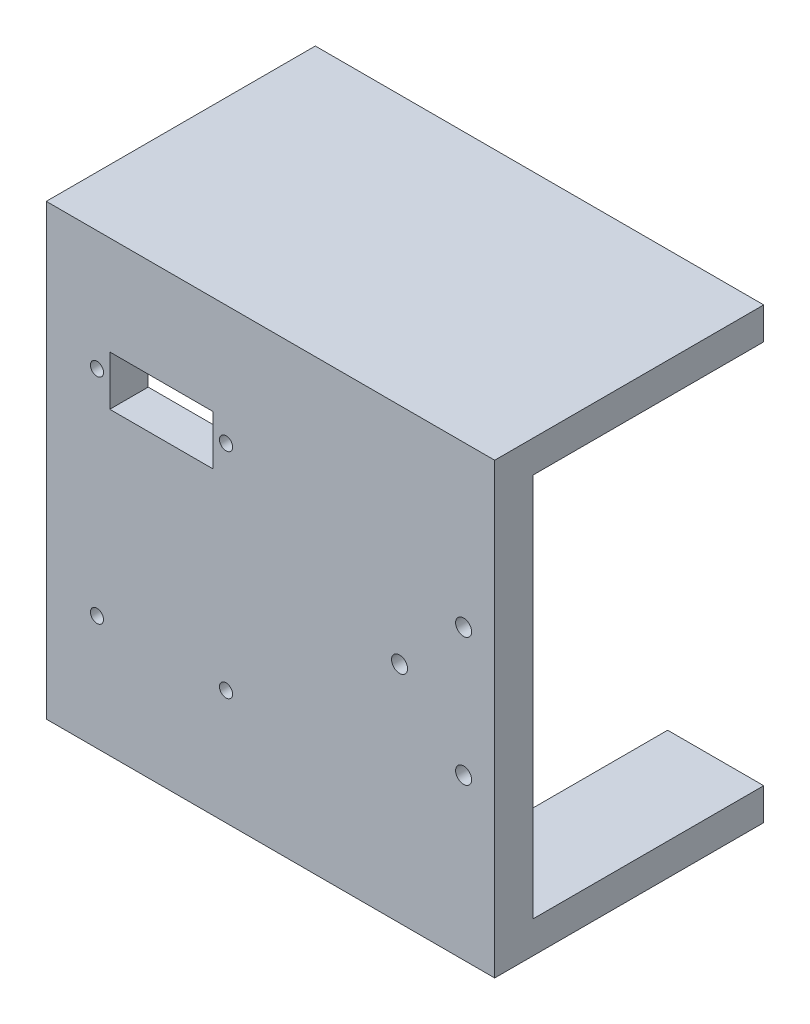
SolidWorks part; units mm, degrees
ref_plane "前视基准面" through (0, 0, 0) normal (0, 0, 1) x (1, 0, 0)
ref_plane "上视基准面" through (0, 0, 0) normal (0, 1, 0) x (1, 0, 0)
ref_plane "右视基准面" through (0, 0, 0) normal (1, 0, 0) x (0, 0, -1)
sketch "Sketch1" plane through (0, 0, 0) normal (0, 0, 1) x (1, 0, 0)
  line L1 (-39.3825, 46.8725) -> (30.6175, 46.8725)
  line L2 (-39.3825, 46.8725) -> (-39.3825, 41.8725)
  line L3 (-39.3825, 41.8725) -> (30.6175, 41.8725)
  line L4 (30.6175, 46.8725) -> (30.6175, 41.8725)
  line L5 (15.6175, -18.1275) -> (30.6175, -18.1275)
  line L6 (15.6175, -18.1275) -> (15.6175, -23.1275)
  line L7 (15.6175, -23.1275) -> (30.6175, -23.1275)
  line L8 (30.6175, -18.1275) -> (30.6175, -23.1275)
  dimension "D1" = 70
  dimension "D2" = 5
  dimension "D3" = 15
  dimension "D4" = 5
  dimension "D5" = 70
extrude "Boss-Extrude1" add sketch "Sketch1" along normal blind 36
sketch "Sketch2" plane through (30.6175, 0, 0) normal (1, 0, 0) x (0, 0, -1)
  line L0 (-36, -23.1275) -> (0, -23.1275) construction
  line L1 (-36, 46.8725) -> (-42, 46.8725)
  line L2 (-36, 46.8725) -> (-36, -23.1275)
  line L3 (-36, -23.1275) -> (-42, -23.1275)
  line L4 (-42, 46.8725) -> (-42, -23.1275)
  dimension "D1" = 6
extrude "Boss-Extrude2" add sketch "Sketch2" against normal up to surface (70 mm away) up to face at (-39.3825, 44.3725, 18)
sketch "Sketch3" plane through (0, 0, 0) normal (0, 0, -1) x (-1, 0, 0)
  line L0 (-30.6175, -23.1275) -> (-30.6175, -18.1275) construction
  line L1 (-30.6175, 41.8725) -> (-30.6175, 46.8725) construction
  line L2 (39.3825, 46.8725) -> (39.3825, 41.8725) construction
  line L3 (-30.6175, 46.8725) -> (39.3825, 46.8725) construction
  line L4 (-15.6175, -23.1275) -> (-30.6175, -23.1275) construction
  circle A0 centre (-23.6175, -20.6275) radius 1
  circle A1 centre (-23.6175, 44.3725) radius 1
  circle A2 centre (32.3825, 44.3725) radius 1
  dimension "D1" = 2
  dimension "D2" = 2
  dimension "D3" = 2
  dimension "D4" = 7
  dimension "D5" = 7
  dimension "D6" = 7
  dimension "D7" = 2.5
  dimension "D8" = 2.5
  dimension "D9" = 2.5
hole_wizard "M2 Tapped Hole1" positions "3DSketch1" profile "Sketch5" tap size "M2" standard "GB"
sketch3d "3DSketch1"
  point P0 (23.6175, 44.3725, 0)
  point P3 (-32.3825, 44.3725, 0)
  point P6 (23.6175, -20.6275, 0)
sketch "Sketch5" plane through (23.6175, 44.3725, 0) normal (1, 0, 0) x (0, 1, 0)
  line L0 (0, 0) -> (0, 5.4807)
  line L1 (0, 5.4807) -> (0.8, 5)
  line L2 (0.8, 5) -> (0.8, 0)
  line L5 (0.8, 0) -> (0, 0)
  line L10 (0, 5.4807) -> (-0.8, 5) construction
  line L11 (0, -6.35) -> (0, 107.95) construction
  dimension "Tap Drill Dia." = 1.6
  dimension "Tap Drill Depth" = 5
  dimension "Drill Angle" = 118
cosmetic thread "Hole Thread1" parameters "D1"=4, "D2"=2
cosmetic thread "Hole Thread2" parameters "D1"=4, "D2"=2
cosmetic thread "Hole Thread3" parameters "D1"=4, "D2"=2
sketch "Sketch6" plane through (0, 0, 42) normal (0, 0, 1) x (1, 0, 0)
  line L0 (30.6175, 46.8725) -> (30.6175, -23.1275) construction
  line L1 (10.6175, -70.6275) -> (30.6175, -70.6275) construction
  line L2 (10.6175, -70.6275) -> (10.6175, 94.3725) construction
  line L3 (10.6175, 94.3725) -> (30.6175, 94.3725) construction
  line L4 (30.6175, -70.6275) -> (30.6175, 94.3725) construction
  line L5 (-22.2951, -23.1275) -> (-22.2951, 46.8725) construction
  line L6 (-39.3825, -23.1275) -> (30.6175, -23.1275) construction
  line L7 (-39.3825, 46.8725) -> (30.6175, 46.8725) construction
  line L8 (25.7675, 1.8725) -> (25.7675, 21.8725) construction
  circle A0 centre (25.7675, 1.8725) radius 1.5
  circle A1 centre (25.7675, 21.8725) radius 1.5
  circle A2 centre (15.7675, 11.8725) radius 1.5
  point P12 (-22.2951, 11.8725)
  point P13 (10.6175, 11.8725)
  point P16 (25.7675, 11.8725)
  dimension "D3" = 3
  dimension "D4" = 3
  dimension "D5" = 3
  dimension "D1" = 165
  dimension "D2" = 20
  dimension "D6" = 10
hole_wizard "M3 Tapped Hole1" positions "3DSketch2" profile "Sketch7" tap size "M3" standard "GB" end condition through all
sketch3d "3DSketch2"
  point P0 (15.7675, 11.8725, 42)
  point P3 (25.7675, 1.8725, 42)
  point P6 (25.7675, 21.8725, 42)
sketch "Sketch7" plane through (15.7675, 11.8725, 42) normal (1, 0, 0) x (0, -1, 0)
  line L0 (0, 0) -> (0, 42)
  line L1 (0, 42) -> (1.25, 42)
  line L2 (1.25, 42) -> (1.25, 0)
  line L5 (1.25, 0) -> (0, 0)
  line L11 (0, -6.35) -> (0, 107.95) construction
  dimension "Thru Tap Drill Dia." = 2.5
  dimension "Thru Tap Drill Depth" = 42
cosmetic thread "Hole Thread4" parameters "D2"=3
cosmetic thread "Hole Thread5" parameters "D2"=3
cosmetic thread "Hole Thread6" parameters "D2"=3
sketch "Sketch8" plane through (0, 0, 42) normal (0, 0, 1) x (1, 0, 0)
  line L1 (-31.4693, 28.1911) -> (-11.3193, 28.1911) construction
  line L2 (-31.4693, 28.1911) -> (-31.4693, -5.2089) construction
  line L3 (-31.4693, -5.2089) -> (-11.3193, -5.2089) construction
  line L4 (-11.3193, 28.1911) -> (-11.3193, -5.2089) construction
  circle A0 centre (-31.4693, 28.1911) radius 1.25
  circle A1 centre (-31.4693, -5.2089) radius 1.25
  circle A2 centre (-11.3193, -5.2089) radius 1.25
  circle A3 centre (-11.3193, 28.1911) radius 1.25
  dimension "D3" = 2.5
  dimension "D4" = 2.5
  dimension "D5" = 2.5
  dimension "D6" = 2.5
  dimension "D1" = 20.15
  dimension "D2" = 33.4
hole_wizard "M2.5 Tapped Hole1" positions "3DSketch3" profile "Sketch9" tap size "M2.5" standard "GB" end condition through all
sketch3d "3DSketch3"
  point P0 (-31.4693, 28.1911, 42)
  point P3 (-11.3193, 28.1911, 42)
  point P6 (-11.3193, -5.2089, 42)
  point P9 (-31.4693, -5.2089, 42)
sketch "Sketch9" plane through (-31.4693, 28.1911, 42) normal (1, 0, 0) x (0, -1, 0)
  line L0 (0, 0) -> (0, 42)
  line L1 (0, 42) -> (1.025, 42)
  line L2 (1.025, 42) -> (1.025, 0)
  line L5 (1.025, 0) -> (0, 0)
  line L11 (0, -6.35) -> (0, 107.95) construction
  dimension "Thru Tap Drill Dia." = 2.05
  dimension "Thru Tap Drill Depth" = 42
cosmetic thread "Hole Thread7" parameters "D2"=2.5
cosmetic thread "Hole Thread8" parameters "D2"=2.5
cosmetic thread "Hole Thread9" parameters "D2"=2.5
cosmetic thread "Hole Thread10" parameters "D2"=2.5
sketch "Sketch10" plane through (0, 0, 42) normal (0, 0, 1) x (1, 0, 0)
  line L0 (-31.4693, 28.1911) -> (-11.3193, 28.1911) construction
  line L2 (-29.4693, 31.4679) -> (-13.3193, 31.4679)
  line L3 (-29.4693, 31.4679) -> (-29.4693, 23.715)
  line L4 (-29.4693, 23.715) -> (-13.3193, 23.715)
  line L5 (-13.3193, 31.4679) -> (-13.3193, 23.715)
  dimension "D1" = 2
  dimension "D2" = 2
extrude "Cut-Extrude1" cut sketch "Sketch10" against normal blind 10
